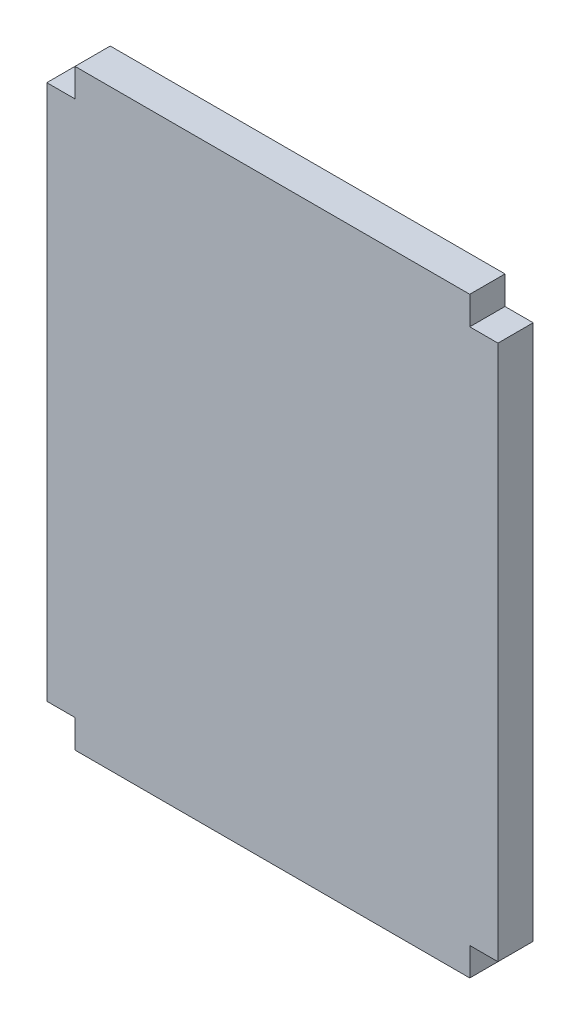
SolidWorks part; units mm, degrees
ref_plane "Front Plane" through (0, 0, 0) normal (0, 0, 1) x (1, 0, 0)
ref_plane "Top Plane" through (0, 0, 0) normal (0, 1, 0) x (1, 0, 0)
ref_plane "Right Plane" through (0, 0, 0) normal (1, 0, 0) x (0, 0, -1)
sketch "Sketch1" plane through (0, 0, 0) normal (0, 0, 1) x (1, 0, 0)
  line L1 (0, 0) -> (640, 0)
  line L2 (0, 0) -> (0, 840)
  line L3 (0, 840) -> (640, 840)
  line L4 (640, 0) -> (640, 840)
  dimension "D1" = 840
  dimension "D2" = 640
extrude "Boss-Extrude1" add sketch "Sketch1" along normal blind 50
sketch "Sketch2" plane through (0, 0, 50) normal (0, 0, 1) x (1, 0, 0)
  line L1 (0, 0) -> (40, 0)
  line L2 (0, 0) -> (0, 40)
  line L3 (0, 40) -> (40, 40)
  line L4 (40, 0) -> (40, 40)
  line L5 (640, 0) -> (600, 0)
  line L6 (640, 0) -> (640, 40)
  line L7 (640, 40) -> (600, 40)
  line L8 (600, 0) -> (600, 40)
  line L9 (640, 840) -> (600, 840)
  line L10 (640, 840) -> (640, 800)
  line L11 (640, 800) -> (600, 800)
  line L12 (600, 840) -> (600, 800)
  line L13 (0, 840) -> (40, 840)
  line L14 (0, 840) -> (0, 800)
  line L15 (0, 800) -> (40, 800)
  line L16 (40, 840) -> (40, 800)
  dimension "D1" = 40
  dimension "D2" = 40
extrude "Cut-Extrude1" cut sketch "Sketch2" against normal up to next
